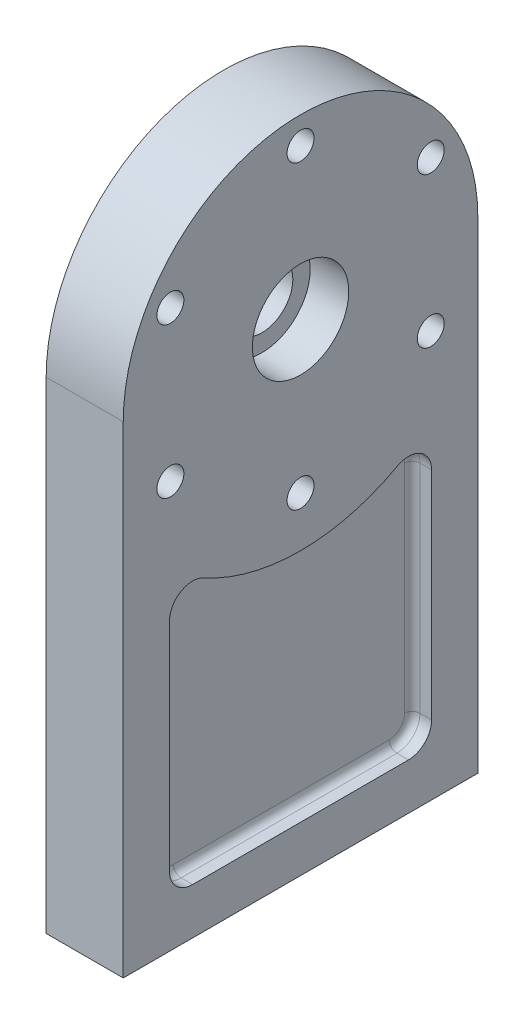
SolidWorks part; units mm, degrees
ref_plane "Front Plane" through (0, 0, 0) normal (0, 0, 1) x (1, 0, 0)
ref_plane "Top Plane" through (0, 0, 0) normal (0, 1, 0) x (1, 0, 0)
ref_plane "Right Plane" through (0, 0, 0) normal (1, 0, 0) x (0, 0, -1)
sketch "Sketch1" plane through (0, 0, 0) normal (1, 0, 0) x (0, 0, -1)
  line L0 (34, -44.5) -> (34, 11.7063)
  line L1 (46, -62.5) -> (-46, -62.5)
  line L2 (46, -62.5) -> (46, 62.5)
  line L4 (-46, -62.5) -> (-46, 62.5)
  line L5 (46, -62.5) -> (-46, 62.5) construction
  line L6 (46, 62.5) -> (-46, -62.5) construction
  line L7 (28, -50.5) -> (-28, -50.5)
  line L8 (-34, -44.5) -> (-34, 11.7063)
  line L9 (34, -50.5) -> (34, 62.5) construction
  line L10 (34, -50.5) -> (-34, -50.5) construction
  line L11 (-34, -50.5) -> (-34, 62.5) construction
  line L12 (0, 62.5) -> (0, 108.5) construction
  arc A0 (-46, 62.5) -> (46, 62.5) centre (0, 62.5) cw
  circle A1 centre (0, 62.5) radius 39 construction
  arc A2 (34, -44.5) -> (28, -50.5) centre (28, -44.5) cw
  arc A3 (-28, -50.5) -> (-34, -44.5) centre (-28, -44.5) cw
  circle A4 centre (0, 62.5) radius 52 construction
  arc A5 (-25.1034, 16.9608) -> (25.1034, 16.9608) centre (0, 62.5) ccw
  arc A6 (25.1034, 16.9608) -> (34, 11.7063) centre (28, 11.7063) cw
  arc A7 (-25.1034, 16.9608) -> (-34, 11.7063) centre (-28, 11.7063) ccw
  circle A8 centre (0, 101.5) radius 3.5
  circle A9 centre (0, 62.5) radius 8
  circle A10 centre (33.775, 82) radius 3.5
  circle A11 centre (33.775, 43) radius 3.5
  circle A12 centre (0, 23.5) radius 3.5
  circle A13 centre (-33.775, 43) radius 3.5
  circle A14 centre (-33.775, 82) radius 3.5
  point P0 (0, 0)
  point P27 (34, 23.1554)
  point P30 (-34, 23.1554)
  point P45 (0, 62.5)
  dimension "D3" = 78
  dimension "D5" = 6
  dimension "D6" = 104
  dimension "D7" = 6
  dimension "D8" = 7
  dimension "D9" = 16
  dimension "D1" = 125
  dimension "D2" = 92
  dimension "D4" = 12
  dimension "D10" = 6
extrude "Boss-Extrude1" add sketch "Sketch1" along normal mid plane 20 contours A5 A7 L8 A3 L7 A2 L0 A6 | A0 L4 L1 L2 A14 A13 A12 A11 A10 A9 A8 A7 A5 A6 L0 A2 L7 A3 L8
sketch "Sketch2" plane through (10, 0, 0) normal (1, 0, 0) x (0, 0, -1)
  line L0 (34, -44.5) -> (34, 11.7063)
  line L1 (46, -62.5) -> (-46, -62.5)
  line L2 (46, -62.5) -> (46, 62.5)
  line L3 (-46, -62.5) -> (-46, 62.5)
  line L4 (46, -62.5) -> (-46, 62.5) construction
  line L5 (46, 62.5) -> (-46, -62.5) construction
  line L6 (28, -50.5) -> (-28, -50.5)
  line L7 (-34, -44.5) -> (-34, 11.7063)
  line L8 (0, 62.5) -> (0, 108.5) construction
  arc A0 (-46, 62.5) -> (46, 62.5) centre (0, 62.5) cw
  circle A1 centre (0, 62.5) radius 39 construction
  arc A2 (34, -44.5) -> (28, -50.5) centre (28, -44.5) cw
  arc A3 (-28, -50.5) -> (-34, -44.5) centre (-28, -44.5) cw
  circle A4 centre (0, 62.5) radius 52 construction
  arc A5 (-25.1034, 16.9608) -> (25.1034, 16.9608) centre (0, 62.5) ccw
  arc A6 (25.1034, 16.9608) -> (34, 11.7063) centre (28, 11.7063) cw
  arc A7 (-25.1034, 16.9608) -> (-34, 11.7063) centre (-28, 11.7063) ccw
  circle A9 centre (0, 62.5) radius 8
  arc A15 (46, 62.5) -> (-46, 62.5) centre (0, 62.5) ccw construction
  point P0 (0, 0)
  point P35 (7.3132, 24.5774)
  dimension "D3" = 78
  dimension "D4" = 6
  dimension "D5" = 104
  dimension "D6" = 6
  dimension "D7" = 12
  dimension "D8" = 16
  dimension "D11" = 52
  dimension "D1" = 125
  dimension "D2" = 92
  dimension "D9" = 12
  dimension "D10" = 12
extrude "Cut-Extrude1" cut sketch "Sketch2" against normal blind 5 contours A5 A7 L7 A3 L6 A2 L0 A6
fillet "Fillet1" radius 2 8 edges at (5, 16.8725, -31.0513) (5, -16.3969, -34) (5, -48.7426, -32.2426) (5, -50.5, 0) (5, -48.7426, 32.2426) (5, -16.3969, 34) (5, 16.8725, 31.0513) (5, 10.5, 0)
sketch "Sketch3" plane through (10, 0, 0) normal (1, 0, 0) x (0, 0, -1)
  circle A3 centre (0, 62.5) radius 12.5
  dimension "D1" = 25
extrude "Cut-Extrude2" cut sketch "Sketch3" against normal blind 10
mirror "Mirror1" about plane through (0, 0, 0) normal (1, 0, 0) of "Fillet1", "Cut-Extrude1"
sketch "Sketch6" plane through (0, -62.5, 0) normal (0, -1, 0) x (1, 0, 0)
  line L0 (0, 46) -> (0, -46) construction
  line L1 (-10, 0) -> (10, 0) construction
  line L4 (-10, 46) -> (-10, -46)
  line L5 (-10, -46) -> (10, -46)
  line L6 (10, -46) -> (10, 46)
  line L7 (10, 46) -> (-10, 46)
  line L8 (-10, 46) -> (-10, -46) construction
  line L9 (-10, -46) -> (10, -46) construction
  line L10 (10, -46) -> (10, 46) construction
  line L11 (10, 46) -> (-10, 46) construction
  circle A0 centre (0, 30) radius 3
  circle A1 centre (0, -30) radius 3
  dimension "D2" = 6
  dimension "D3" = 60
  dimension "D4" = 30
  dimension "D1" = 0
extrude "Cut-Extrude3" cut sketch "Sketch6" against normal blind 10
